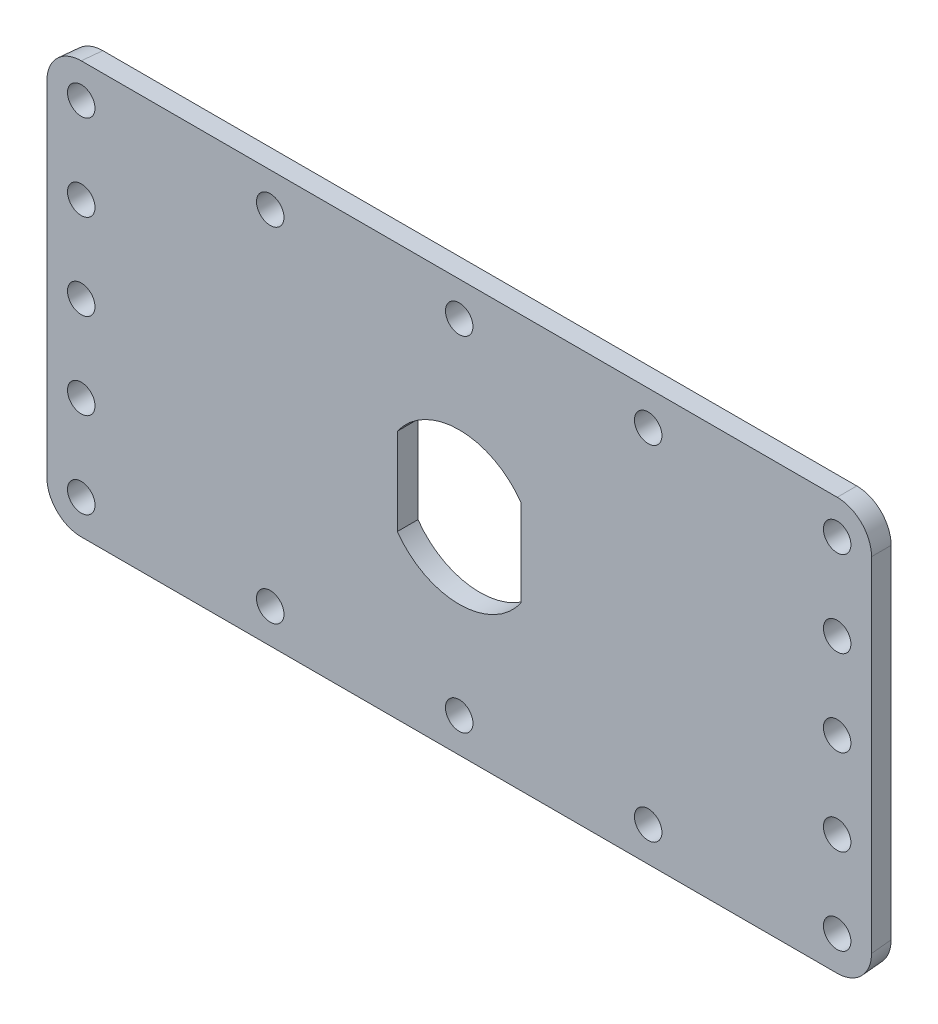
SolidWorks part; units mm, degrees
ref_plane "Front Plane" through (0, 0, 0) normal (0, 0, 1) x (1, 0, 0)
ref_plane "Top Plane" through (0, 0, 0) normal (0, 1, 0) x (1, 0, 0)
ref_plane "Right Plane" through (0, 0, 0) normal (1, 0, 0) x (0, 0, -1)
sketch "Sketch1" plane through (0, 0, 0) normal (0, 0, 1) x (1, 0, 0)
  line L1 (-60, -30) -> (60, -30)
  line L2 (-60, -30) -> (-60, 30)
  line L3 (-60, 30) -> (60, 30)
  line L4 (60, -30) -> (60, 30)
  line L5 (-60, -30) -> (60, 30) construction
  line L6 (-60, 30) -> (60, -30) construction
  point P0 (0, 0)
  dimension "D1" = 120
  dimension "D2" = 60
extrude "Boss-Extrude1" add sketch "Sketch1" against normal blind 3 draft 2.862
sketch "Sketch5" plane through (0, 0, 0) normal (0, 0, 1) x (1, 0, 0)
  line L0 (-9, 6.3246) -> (-9, -6.3246)
  line L2 (9, -6.3246) -> (9, 6.3246)
  arc A0 (-9, -6.3246) -> (9, -6.3246) centre (0, 0) ccw
  arc A1 (9, 6.3246) -> (-9, 6.3246) centre (0, 0) ccw
  point P1 (10.796, -2.1088)
  dimension "D2" = 22
  dimension "D1" = 18
extrude "Cut-Extrude4" cut sketch "Sketch5" against normal blind 25
fillet "Fillet1" radius 5 4 edges at (59.925, -29.925, -1.5) (59.925, 29.925, -1.5) (-59.925, 29.925, -1.5) (-59.925, -29.925, -1.5)
sketch "Sketch6" plane through (0, 0, 0) normal (0, 0, 1) x (1, 0, 0)
  line L0 (-60, 25.0062) -> (-60, -25.0062) construction
  line L1 (55.0062, 30) -> (-55.0062, 30) construction
  line L2 (-60, 0) -> (60, 0) construction
  line L3 (60, -25.0062) -> (60, 25.0062) construction
  line L4 (0, 30) -> (0, -30) construction
  line L5 (-55.0062, -30) -> (55.0062, -30) construction
  circle A0 centre (-55, 25) radius 2
  circle A1 centre (-27.5, 25) radius 2
  circle A2 centre (0, 25) radius 2
  circle A3 centre (27.5, 25) radius 2
  circle A4 centre (55, 25) radius 2
  circle A5 centre (55, -25) radius 2
  circle A6 centre (27.5, -25) radius 2
  circle A7 centre (0, -25) radius 2
  circle A8 centre (-27.5, -25) radius 2
  circle A9 centre (-55, -25) radius 2
  circle A10 centre (-55, 12.5) radius 2
  circle A11 centre (-55, 0) radius 2
  circle A12 centre (-55, -12.5) radius 2
  circle A13 centre (55, -12.5) radius 2
  circle A14 centre (55, 0) radius 2
  circle A15 centre (55, 12.5) radius 2
  dimension "D3" = 4
  dimension "D1" = 5
  dimension "D2" = 5
  dimension "D5" = 110
  dimension "D7" = 37.5
  dimension "D4" = 5
  dimension "D6" = 4
extrude "Cut-Extrude5" cut sketch "Sketch6" against normal up to next
equation "\"D3@Boss-Extrude1\"=atn(10/200deg)"
